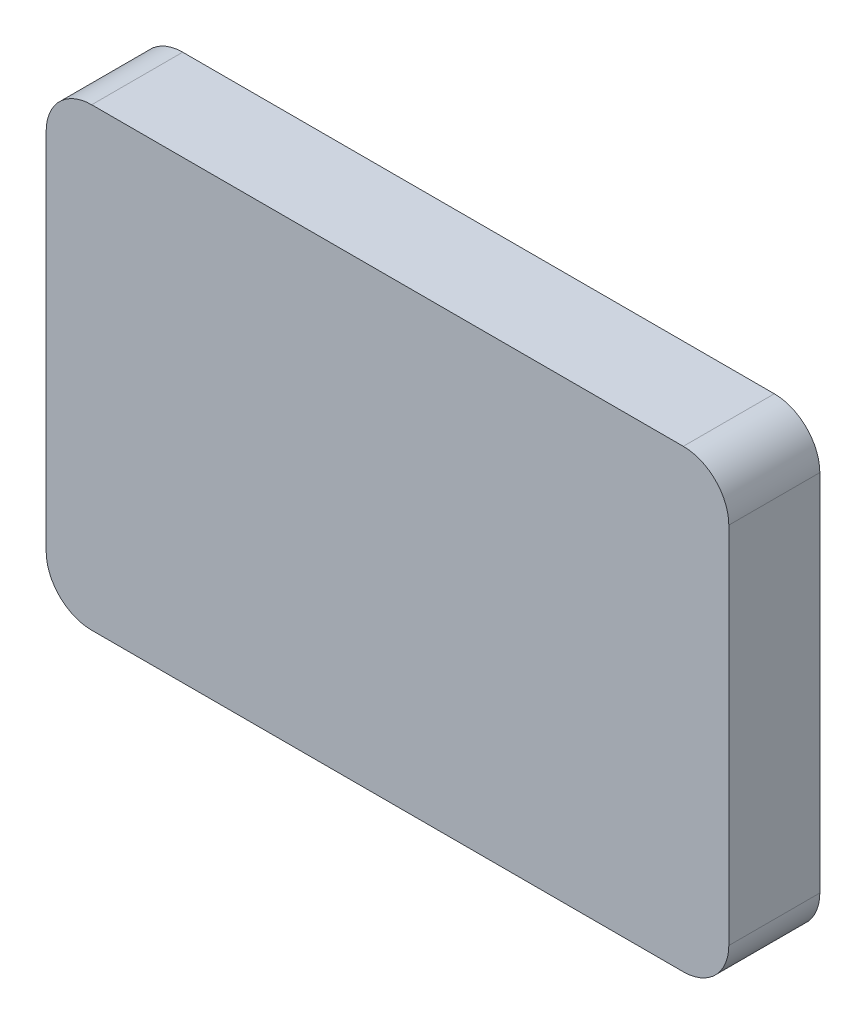
SolidWorks part; units mm, degrees
ref_plane "Front Plane" through (0, 0, 0) normal (0, 0, 1) x (1, 0, 0)
ref_plane "Top Plane" through (0, 0, 0) normal (0, 1, 0) x (1, 0, 0)
ref_plane "Right Plane" through (0, 0, 0) normal (1, 0, 0) x (0, 0, -1)
sketch "Sketch1" plane through (0, 0, 0) normal (0, 0, 1) x (1, 0, 0)
  line L1 (0, 0) -> (15, 0)
  line L2 (0, 0) -> (0, 10)
  line L3 (0, 10) -> (15, 10)
  line L4 (15, 0) -> (15, 10)
  line L5 (15, 6.25) -> (15, 3.9873)
  line L24 (15, 10) -> (-49985, 10) construction
  dimension "D1" = 10
  dimension "D2" = 15
extrude "Boss-Extrude2" add sketch "Sketch1" along normal blind 2
fillet "Fillet1" radius 1 4 edges at (0, 0, 1) (15, 0, 1) (15, 10, 1) (0, 10, 1)
